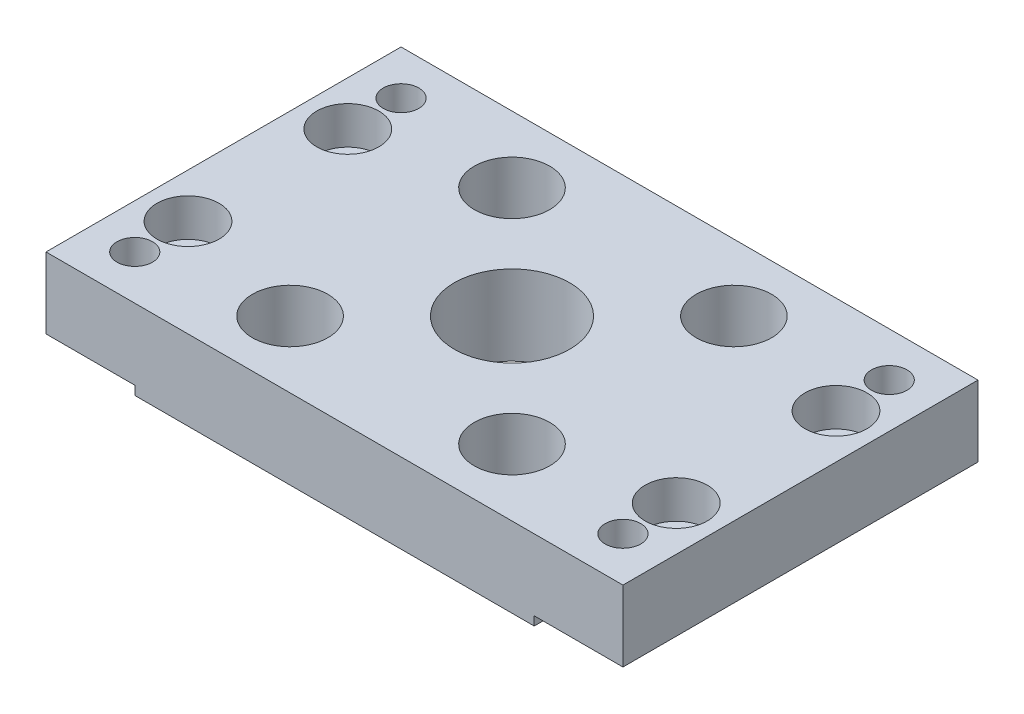
SolidWorks part; units mm, degrees
ref_plane "Alzado" through (0, 0, 0) normal (0, 0, 1) x (1, 0, 0)
ref_plane "Planta" through (0, 0, 0) normal (0, 1, 0) x (1, 0, 0)
ref_plane "Vista lateral" through (0, 0, 0) normal (1, 0, 0) x (0, 0, -1)
sketch "Croquis1" plane through (0, 0, 0) normal (0, 0, 1) x (1, 0, 0)
  line L0 (65, 0) -> (-65, 0)
  line L1 (-65, 0) -> (-65, -16)
  line L2 (-65, -16) -> (-45, -16)
  line L3 (-45, -16) -> (-45, -18)
  line L4 (-45, -18) -> (45, -18)
  line L5 (45, -18) -> (45, -16)
  line L6 (45, -16) -> (65, -16)
  line L7 (65, -16) -> (65, 0)
  dimension "D1" = 65
  dimension "D2" = 65
  dimension "D3" = 16
  dimension "D4" = 16
  dimension "D5" = 18
  dimension "D6" = 20
  dimension "D7" = 20
extrude "Saliente-Extruir1" add sketch "Croquis1" against normal blind 80
sketch "Croquis2" plane through (0, 0, 0) normal (0, 1, 0) x (1, 0, 0)
  line L0 (65, 0) -> (-65, 0) construction
  line L1 (-65, 80) -> (-65, 0) construction
  line L2 (65, 80) -> (65, 0) construction
  circle A0 centre (0, 40) radius 13
  circle A1 centre (-55, 70) radius 4
  circle A2 centre (-55, 10) radius 4
  circle A3 centre (55, 10) radius 4
  circle A4 centre (55, 70) radius 4
  circle A5 centre (-55, 58) radius 4.5
  circle A6 centre (-55, 22) radius 4.5
  circle A7 centre (55, 58) radius 4.5
  circle A8 centre (55, 22) radius 4.5
  dimension "D2" = 26
  dimension "D3" = 8
  dimension "D4" = 9
  dimension "D9" = 10
  dimension "D10" = 10
  dimension "D1" = 40
  dimension "D5" = 30
  dimension "D6" = 30
  dimension "D7" = 18
  dimension "D8" = 18
extrude "Cortar-Extruir1" cut sketch "Croquis2" against normal through all
sketch "Croquis4" plane through (0, 0, 0) normal (0, 1, 0) x (1, 0, 0)
  circle A0 centre (-55, 58) radius 7
  circle A1 centre (-55, 22) radius 7
  circle A2 centre (55, 58) radius 7
  circle A3 centre (55, 22) radius 7
  dimension "D1" = 14
extrude "Cortar-Extruir2" cut sketch "Croquis4" against normal blind 8.5
sketch "Croquis5" plane through (0, 0, 0) normal (0, 1, 0) x (1, 0, 0)
  circle A0 centre (-25, 65) radius 5.5
  circle A1 centre (-25, 15) radius 5.5
  circle A2 centre (25, 15) radius 5.5
  circle A3 centre (25, 65) radius 5.5
  circle A4 centre (0, 40) radius 13 construction
  dimension "D1" = 25
  dimension "D2" = 25
  dimension "D3" = 25
  dimension "D4" = 25
  dimension "D5" = 25
  dimension "D6" = 25
  dimension "D7" = 11
  dimension "D8" = 11
  dimension "D9" = 11
  dimension "D10" = 11
  dimension "D11" = 25
  dimension "D12" = 25
extrude "Cortar-Extruir3" cut sketch "Croquis5" against normal up to next
sketch "Croquis6" plane through (0, 0, 0) normal (0, 1, 0) x (1, 0, 0)
  circle A0 centre (-25, 65) radius 8.5
  circle A1 centre (-25, 15) radius 8.5
  circle A2 centre (25, 15) radius 8.5
  circle A3 centre (25, 65) radius 8.5
  dimension "D1" = 17
  dimension "D2" = 17
  dimension "D3" = 17
  dimension "D4" = 17
extrude "Cortar-Extruir4" cut sketch "Croquis6" against normal blind 13
sketch "Croquis7" plane through (0, 0, -80) normal (0, 0, -1) x (-1, 0, 0)
  line L0 (-65, 0) -> (65, 0) construction
  circle A1 centre (38, -8) radius 3
  circle A2 centre (-38, -8) radius 3
  point P9 (0, 0)
  point P10 (0, 0)
  dimension "D2" = 6
  dimension "D3" = 6
  dimension "D4" = 38
  dimension "D6" = 8
  dimension "D7" = 8
  dimension "D5" = 38
extrude "Cortar-Extruir5" cut sketch "Croquis7" against normal blind 30
